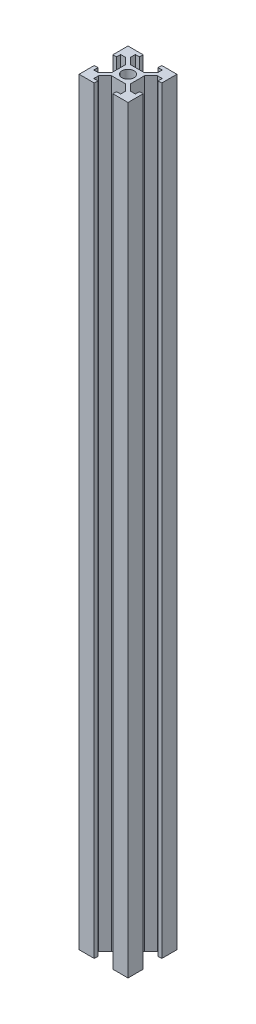
SolidWorks part; units mm, degrees
material "7075-T6 (SN)"
ref_plane "前视基准面" through (0, 0, 0) normal (0, 0, 1) x (1, 0, 0)
ref_plane "上视基准面" through (0, 0, 0) normal (0, 1, 0) x (1, 0, 0)
ref_plane "右视基准面" through (0, 0, 0) normal (1, 0, 0) x (0, 0, -1)
sketch "草图1" plane through (0, 0, 0) normal (0, 1, 0) x (1, 0, 0)
  line L0 (-6.5607, 5.5) -> (-3.9, 2.8393)
  line L1 (-10, 10) -> (10, 10)
  line L2 (-10, 10) -> (-10, -10)
  line L3 (-10, -10) -> (10, -10)
  line L4 (10, 10) -> (10, -10)
  line L5 (-10, 10) -> (10, -10) construction
  line L6 (-10, -10) -> (10, 10) construction
  line L7 (-3.9, 3.9) -> (3.9, 3.9)
  line L8 (-3.9, 3.9) -> (-3.9, -3.9)
  line L9 (-3.9, -3.9) -> (3.9, -3.9)
  line L10 (3.9, 3.9) -> (3.9, -3.9)
  line L11 (-3.9, 3.9) -> (3.9, -3.9) construction
  line L12 (-3.9, -3.9) -> (3.9, 3.9) construction
  line L13 (-10, 10) -> (-5.5, 10)
  line L14 (-10, 10) -> (-10, 5.5)
  line L15 (-10, 5.5) -> (-5.5, 5.5)
  line L16 (-5.5, 10) -> (-5.5, 5.5)
  line L17 (-10, 5.5) -> (-8.5, 5.5)
  line L18 (-10, 5.5) -> (-10, 3.8)
  line L19 (-10, 3.8) -> (-8.5, 3.8)
  line L20 (-8.5, 5.5) -> (-8.5, 3.8)
  line L21 (-5.5, 6.5607) -> (-2.8393, 3.9)
  line L22 (-3.8, 10) -> (-3.8, 8.5)
  line L23 (-5.5, 8.5) -> (-3.8, 8.5)
  line L24 (0, 10) -> (0, -10) construction
  line L25 (5.5, 8.5) -> (3.8, 8.5)
  line L26 (3.8, 10) -> (3.8, 8.5)
  line L27 (5.5, 6.5607) -> (2.8393, 3.9)
  line L28 (6.5607, 5.5) -> (3.9, 2.8393)
  line L29 (10, 3.8) -> (8.5, 3.8)
  line L30 (8.5, 5.5) -> (8.5, 3.8)
  line L31 (10, 5.5) -> (8.5, 5.5)
  line L32 (10, 5.5) -> (10, 3.8)
  line L33 (10, 5.5) -> (5.5, 5.5)
  line L34 (5.5, 10) -> (5.5, 5.5)
  line L35 (10, 10) -> (5.5, 10)
  line L36 (10, 10) -> (10, 5.5)
  line L37 (-10, 0) -> (10, 0) construction
  line L38 (-10, -3.8) -> (-8.5, -3.8)
  line L39 (-8.5, -5.5) -> (-8.5, -3.8)
  line L40 (-10, -5.5) -> (-5.5, -5.5)
  line L41 (-6.5607, -5.5) -> (-3.9, -2.8393)
  line L42 (-5.5, -6.5607) -> (-2.8393, -3.9)
  line L43 (-5.5, -10) -> (-5.5, -5.5)
  line L44 (-5.5, -8.5) -> (-3.8, -8.5)
  line L45 (-3.8, -10) -> (-3.8, -8.5)
  line L46 (3.8, -10) -> (3.8, -8.5)
  line L47 (6.5607, -5.5) -> (3.9, -2.8393)
  line L48 (5.5, -6.5607) -> (2.8393, -3.9)
  line L49 (-10, 10) -> (10, 10)
  line L50 (-10, -10) -> (10, -10)
  line L51 (5.5, -8.5) -> (3.8, -8.5)
  line L52 (5.5, -10) -> (5.5, -5.5)
  line L53 (10, -5.5) -> (5.5, -5.5)
  line L54 (10, -3.8) -> (8.5, -3.8)
  line L55 (8.5, -5.5) -> (8.5, -3.8)
  circle A0 centre (0, 0) radius 2.5
  dimension "D1" = 5
  dimension "D2" = 20
  dimension "D3" = 20
  dimension "D4" = 7.8
  dimension "D5" = 4.5
  dimension "D6" = 1.7
  dimension "D7" = 0.75
  dimension "D8" = 1.5
extrude "凸台-拉伸1" add sketch "草图1" along normal blind 310 contours L1 L34 L33 L31 L4 | L4 L31 L30 L29 | L34 L27 L7 L10 L28 L33 | L34 L1 L26 L25 | L10 L7 L8 L9 A0 | L16 L23 L22 L1 | L16 L1 L2 L15 | L20 L15 L2 L19 | L21 L16 L15 L0 L8 L7 | L3 L43 L40 L2 | L3 L45 L44 L43 | L2 L40 L39 L38 | L43 L42 L9 L8 L41 L40 | L53 L47 L10 L9 L48 L52 | L4 L53 L52 L50 | L55 L53 L4 L54 | L3 L52 L51 L46
